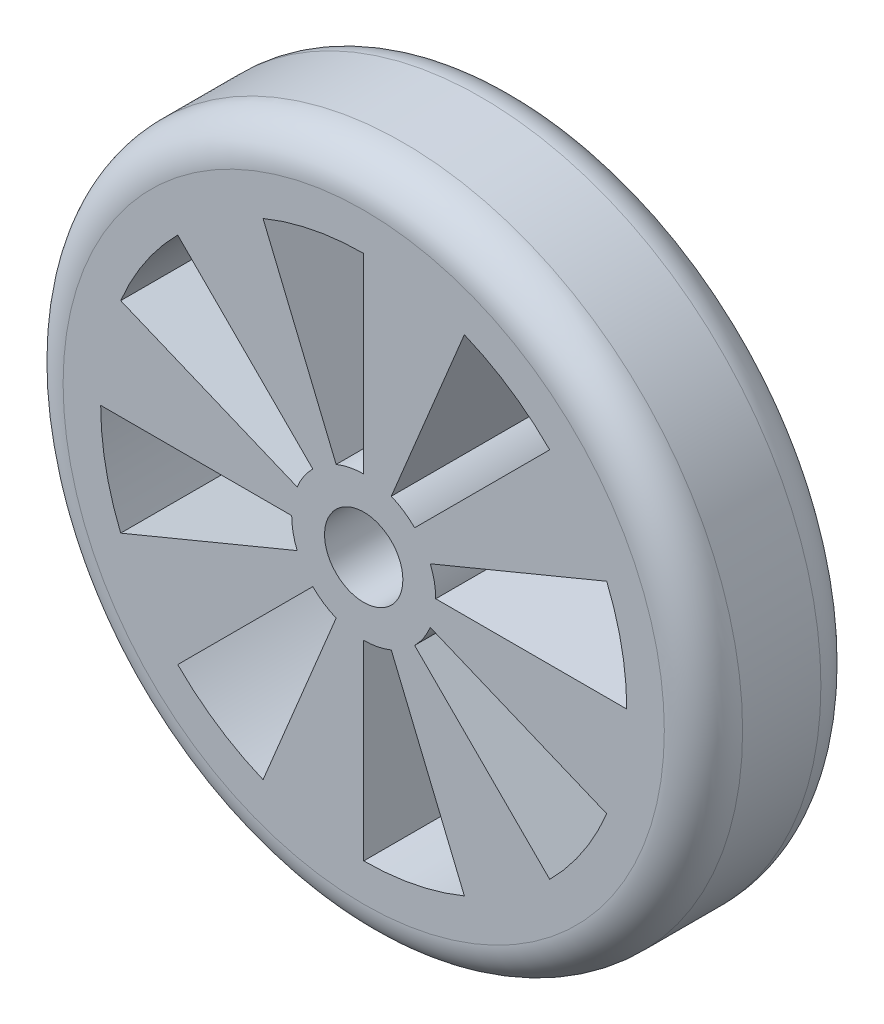
SolidWorks part; units mm, degrees
ref_plane "Front Plane" through (0, 0, 0) normal (0, 0, 1) x (1, 0, 0)
ref_plane "Top Plane" through (0, 0, 0) normal (0, 1, 0) x (1, 0, 0)
ref_plane "Right Plane" through (0, 0, 0) normal (1, 0, 0) x (0, 0, -1)
sketch "Sketch1" plane through (0, 0, 0) normal (0, 0, 1) x (1, 0, 0)
  circle A0 centre (0, 0) radius 25
  circle A1 centre (0, 0) radius 46
  circle A2 centre (0, 0) radius 169
  circle A3 centre (0, 0) radius 217
  dimension "D1" = 434
  dimension "D2" = 50
  dimension "D3" = 92
  dimension "D4" = 338
extrude "Boss-Extrude1" add sketch "Sketch1" along normal blind 100 contours A3
fillet "Fillet1" radius 25 1 edges at (217, 0, 100)
fillet "Fillet2" radius 25 1 edges at (217, 0, 0)
sketch "Sketch3" plane through (0, 0, 0) normal (0, 0, 1) x (1, 0, 0)
  line L0 (0, 46) -> (0, 168)
  line L1 (17.6034, 42.4985) -> (64.2908, 155.2118)
  line L2 (32.5269, 32.5269) -> (118.7939, 118.7939)
  line L3 (42.4985, 17.6034) -> (155.2118, 64.2908)
  line L4 (46, 0) -> (168, 0)
  line L5 (42.4985, -17.6034) -> (155.2118, -64.2908)
  line L6 (32.5269, -32.5269) -> (118.7939, -118.7939)
  line L7 (17.6034, -42.4985) -> (64.2908, -155.2118)
  line L8 (0, -46) -> (0, -168)
  line L9 (-17.6034, -42.4985) -> (-64.2908, -155.2118)
  line L10 (-32.5269, -32.5269) -> (-118.7939, -118.7939)
  line L11 (-42.4985, -17.6034) -> (-155.2118, -64.2908)
  line L12 (-46, 0) -> (-168, 0)
  line L13 (-42.4985, 17.6034) -> (-155.2118, 64.2908)
  line L14 (-32.5269, 32.5269) -> (-118.7939, 118.7939)
  line L15 (-17.6034, 42.4985) -> (-64.2908, 155.2118)
  line L16 (-32.5269, 32.5269) -> (-118.7939, 118.7939) [skipped]
  line L17 (-42.4985, 17.6034) -> (-155.2118, 64.2908) [skipped]
  line L18 (-46, 0) -> (-168, 0) [skipped]
  line L19 (-42.4985, -17.6034) -> (-155.2118, -64.2908) [skipped]
  line L20 (-32.5269, -32.5269) -> (-118.7939, -118.7939) [skipped]
  line L21 (-17.6034, -42.4985) -> (-64.2908, -155.2118) [skipped]
  line L22 (0, -46) -> (0, -168) [skipped]
  line L23 (17.6034, -42.4985) -> (64.2908, -155.2118) [skipped]
  line L24 (32.5269, -32.5269) -> (118.7939, -118.7939) [skipped]
  line L25 (42.4985, -17.6034) -> (155.2118, -64.2908) [skipped]
  line L26 (46, 0) -> (168, 0) [skipped]
  line L27 (42.4985, 17.6034) -> (155.2118, 64.2908) [skipped]
  line L28 (32.5269, 32.5269) -> (118.7939, 118.7939) [skipped]
  line L29 (17.6034, 42.4985) -> (64.2908, 155.2118) [skipped]
  arc A0 (0, 46) -> (-17.6034, 42.4985) centre (0, 0) ccw
  arc A1 (0, 168) -> (-64.2908, 155.2118) centre (0, 0) ccw
  arc A2 (118.7939, 118.7939) -> (64.2908, 155.2118) centre (0, 0) ccw
  arc A3 (32.5269, 32.5269) -> (17.6034, 42.4985) centre (0, 0) ccw
  arc A4 (168, 0) -> (155.2118, 64.2908) centre (0, 0) ccw
  arc A5 (46, 0) -> (42.4985, 17.6034) centre (0, 0) ccw
  arc A6 (118.7939, -118.7939) -> (155.2118, -64.2908) centre (0, 0) ccw
  arc A7 (32.5269, -32.5269) -> (42.4985, -17.6034) centre (0, 0) ccw
  arc A8 (0, -168) -> (64.2908, -155.2118) centre (0, 0) ccw
  arc A9 (0, -46) -> (17.6034, -42.4985) centre (0, 0) ccw
  arc A10 (-118.7939, -118.7939) -> (-64.2908, -155.2118) centre (0, 0) ccw
  arc A11 (-32.5269, -32.5269) -> (-17.6034, -42.4985) centre (0, 0) ccw
  arc A12 (-168, 0) -> (-155.2118, -64.2908) centre (0, 0) ccw
  arc A13 (-46, 0) -> (-42.4985, -17.6034) centre (0, 0) ccw
  arc A14 (-118.7939, 118.7939) -> (-155.2118, 64.2908) centre (0, 0) ccw
  arc A15 (-32.5269, 32.5269) -> (-42.4985, 17.6034) centre (0, 0) ccw
  point P21 (0, 0)
  point P66 (0, 0)
  dimension "D2" = 92
  dimension "D3" = 336
  dimension "D1" = 16
  dimension "D4" = 8
extrude "Cut-Extrude4" cut sketch "Sketch3" against normal blind 20000 and the other way blind 20000 contours A13 L12 A12 L11 | A9 L8 A8 L7 | A7 L6 A6 L5 | A5 L4 A4 L3 | A3 L2 A2 L1 | L0 A1 L15 A0 | L13 A14 L14 A15 | L9 A10 L10 A11
sketch "Sketch8" plane through (0, 0, 0) normal (0, 0, 1) x (1, 0, 0)
  circle A0 centre (0, 0) radius 25
  dimension "D1" = 50
extrude "Cut-Extrude5" cut sketch "Sketch8" against normal blind 20000 and the other way blind 20000
